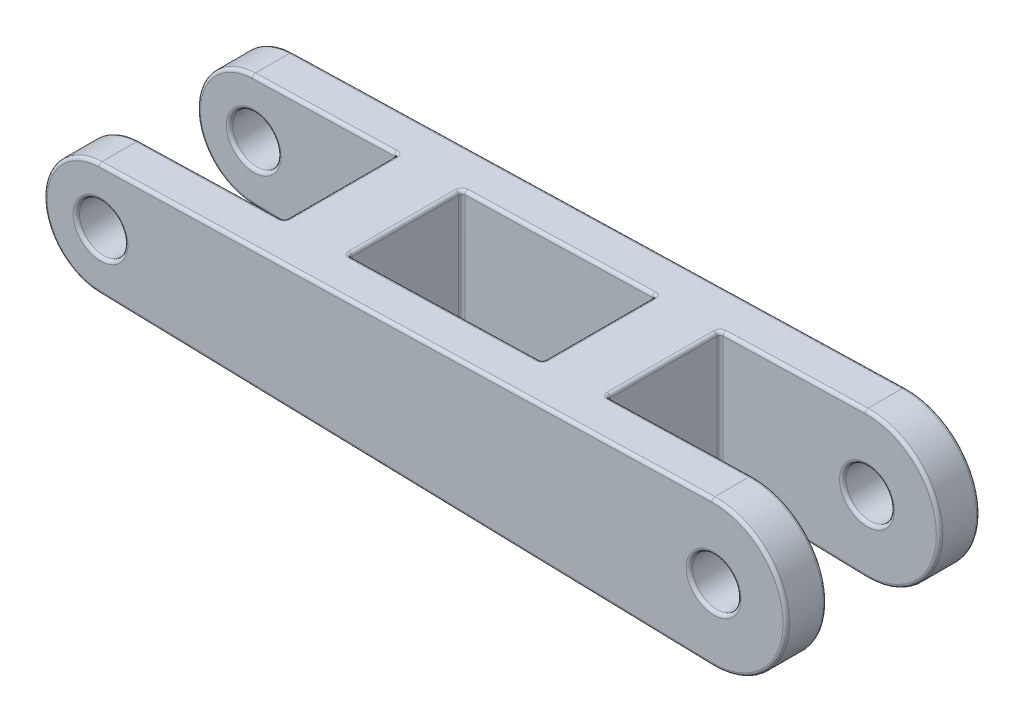
SolidWorks part; units mm, degrees
ref_plane "Front Plane" through (0, 0, 0) normal (0, 0, 1) x (1, 0, 0)
ref_plane "Top Plane" through (0, 0, 0) normal (0, 1, 0) x (1, 0, 0)
ref_plane "Right Plane" through (0, 0, 0) normal (1, 0, 0) x (0, 0, -1)
sketch "Sketch1" plane through (0, 0, 0) normal (0, 0, 1) x (1, 0, 0)
  line L0 (-19.0461, 1.7494) -> (-0.0592, 2.2492)
  line L1 (-19.0461, -1.7494) -> (-0.0592, -2.2492)
  arc A0 (-0.0592, -2.2492) -> (-0.0592, 2.2492) centre (0, 0) ccw
  arc A1 (-19.0461, 1.7494) -> (-19.0461, -1.7494) centre (-19, 0) ccw
  circle A2 centre (-19, 0) radius 0.75
  circle A3 centre (0, 0) radius 0.75
  dimension "D1" = 4.5
  dimension "D2" = 3.5
  dimension "D4" = 1.5
  dimension "D3" = 19
extrude "Boss-Extrude1" add sketch "Sketch1" along normal mid plane 6
sketch "Sketch2" plane through (0, 0, 0) normal (0, 1, 0) x (1, 0, 0)
  line L0 (-9.5526, 3) -> (-9.5526, 5.0934) construction
  line L1 (-14.5526, -1.75) -> (-22.5526, -1.75)
  line L2 (-14.5526, -1.75) -> (-14.5526, 1.75)
  line L3 (-14.5526, 1.75) -> (-22.5526, 1.75)
  line L4 (-22.5526, -1.75) -> (-22.5526, 1.75)
  line L5 (-14.5526, -1.75) -> (-22.5526, 1.75) construction
  line L6 (-14.5526, 1.75) -> (-22.5526, -1.75) construction
  line L7 (-6.5526, -1.75) -> (-12.5526, -1.75)
  line L8 (-6.5526, -1.75) -> (-6.5526, 1.75)
  line L9 (-6.5526, 1.75) -> (-12.5526, 1.75)
  line L10 (-12.5526, -1.75) -> (-12.5526, 1.75)
  line L11 (-6.5526, -1.75) -> (-12.5526, 1.75) construction
  line L12 (-6.5526, 1.75) -> (-12.5526, -1.75) construction
  line L13 (3.4474, -1.75) -> (-4.5526, -1.75)
  line L14 (3.4474, -1.75) -> (3.4474, 1.75)
  line L15 (3.4474, 1.75) -> (-4.5526, 1.75)
  line L16 (-4.5526, -1.75) -> (-4.5526, 1.75)
  line L17 (3.4474, -1.75) -> (-4.5526, 1.75) construction
  line L18 (3.4474, 1.75) -> (-4.5526, -1.75) construction
  line L19 (-0.0592, 3) -> (-19.0461, 3) construction
  point P0 (-18.5526, 0)
  point P5 (-9.5526, 0)
  point P10 (-0.5526, 0)
  point P16 (-14.5526, 0)
  point P17 (-4.5526, 0)
  dimension "D1" = 8
  dimension "D2" = 2
  dimension "D3" = 10
  dimension "D4" = 3.5
  dimension "D5" = 2
extrude "Cut-Extrude1" cut sketch "Sketch2" against normal through all both and the other way through all
fillet "Fillet1" radius 0.1 48 edges at (-4.5526, 0, 1.75) (-4.5526, 0, -1.75) (-12.5526, 0, 1.75) (-6.5526, 0, 1.75) (-6.5526, 0, -1.75) (-12.5526, 0, -1.75) (-14.5526, 0, 1.75) (-14.5526, 0, -1.75) (0.75, 0, 1.75) (-2.3059, 2.1901, 1.75) (2.25, 0, 1.75) (-2.3059, -2.1901, 1.75) (-0.75, 0, -1.75) (-2.3059, 2.1901, -1.75) (2.25, 0, -1.75) (-2.3059, -2.1901, -1.75) (-18.25, 0, 1.75) (-16.7993, 1.8085, 1.75) (-20.75, 0, 1.75) (-16.7993, -1.8085, 1.75) (-19.75, 0, -1.75) (-20.75, 0, -1.75) (-16.7993, -1.8085, -1.75) (-4.5526, -2.1309, 0) (-9.5526, -1.9993, 1.75) (-6.5526, -2.0783, 0) (-9.5526, -1.9993, -1.75) (-12.5526, -1.9203, 0) (-14.5526, -1.8677, 0) (0.75, 0, -3) (0.75, 0, 3) (-18.25, 0, -3) (-18.25, 0, 3) (-20.75, 0, -3) (-9.5526, -1.9993, -3) (2.25, 0, -3) (-9.5526, 1.9993, -3) (-20.75, 0, 3) (-9.5526, -1.9993, 3) (2.25, 0, 3) (-9.5526, 1.9993, 3) (-4.5526, 2.1309, 0) (-9.5526, 1.9993, 1.75) (-6.5526, 2.0783, 0) (-9.5526, 1.9993, -1.75) (-12.5526, 1.9203, 0) (-14.5526, 1.8677, 0) (-16.7993, 1.8085, -1.75)
